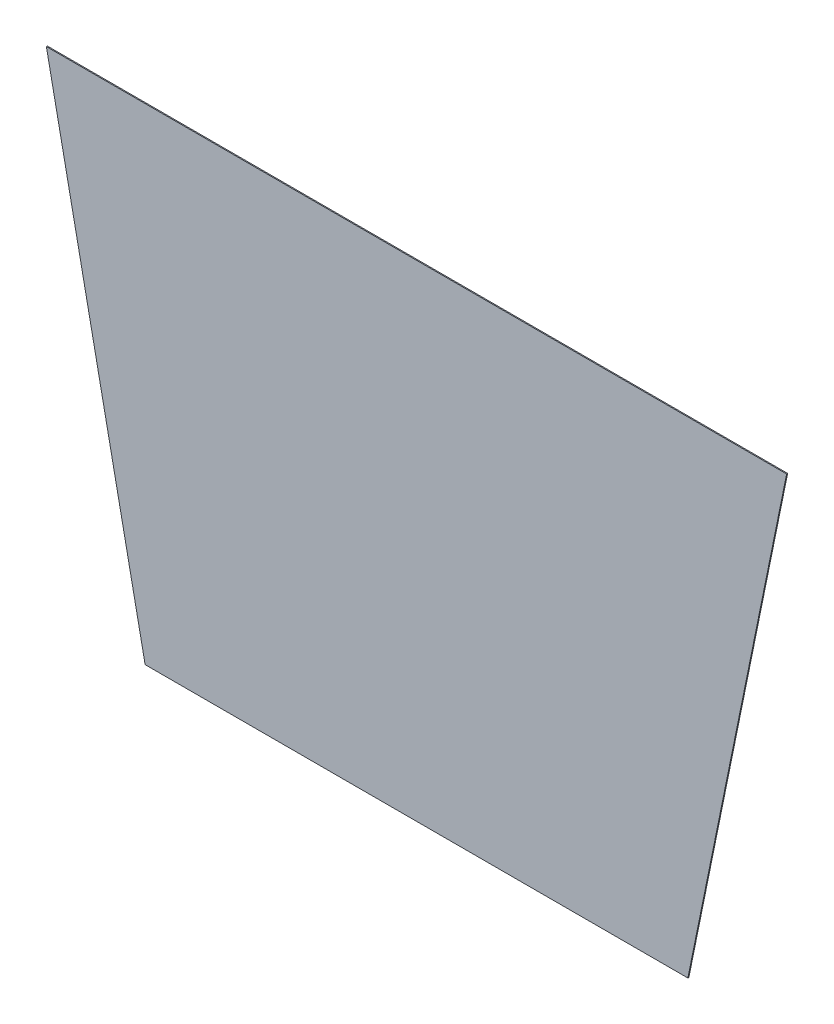
SolidWorks part; units mm, degrees
ref_plane "Front Plane" through (0, 0, 0) normal (0, 0, 1) x (1, 0, 0)
ref_plane "Top Plane" through (0, 0, 0) normal (0, 1, 0) x (1, 0, 0)
ref_plane "Right Plane" through (0, 0, 0) normal (1, 0, 0) x (0, 0, -1)
sketch "Sketch1" plane through (0, 0, 0) normal (0, 0, 1) x (1, 0, 0)
  line L0 (-371.2575, -179.1382) -> (438.7425, -179.1382)
  line L1 (-371.2575, -179.1382) -> (-518.6632, 546.0318)
  line L2 (438.7425, -179.1382) -> (586.1482, 546.0318)
  line L3 (586.1482, 546.0318) -> (-518.6632, 546.0318)
  dimension "D1" = 810
  dimension "D2" = 101.49
  dimension "D3" = 101.49
  dimension "D4" = 740
  dimension "D5" = 740
extrude "Boss-Extrude1" add sketch "Sketch1" along normal blind 1.5
